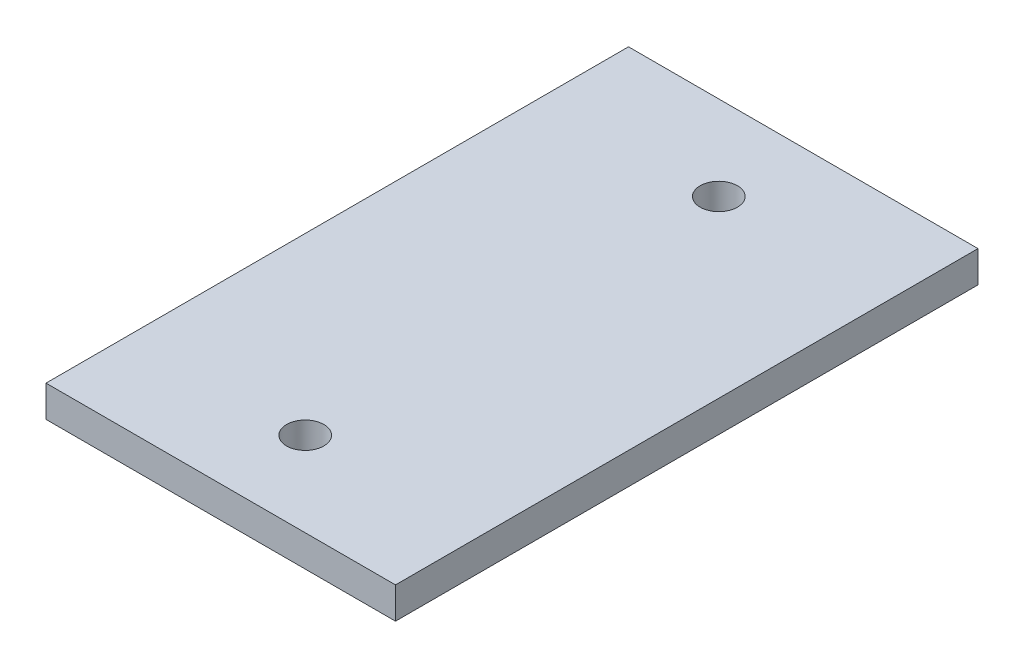
SolidWorks part; units mm, degrees
ref_plane "Front Plane" through (0, 0, 0) normal (0, 0, 1) x (1, 0, 0)
ref_plane "Top Plane" through (0, 0, 0) normal (0, 1, 0) x (1, 0, 0)
ref_plane "Right Plane" through (0, 0, 0) normal (1, 0, 0) x (0, 0, -1)
sketch "Sketch1" plane through (0, 0, 0) normal (0, 1, 0) x (1, 0, 0)
  line L0 (0, -2.0528) -> (0, 25.6838) construction
  line L1 (-15, 25) -> (15, 25)
  line L2 (-15, 25) -> (-15, -25)
  line L3 (-15, -25) -> (15, -25)
  line L4 (15, 25) -> (15, -25)
  line L5 (-15, 25) -> (15, -25) construction
  line L6 (-15, -25) -> (15, 25) construction
  line L7 (0, 0) -> (-35.0245, 0) construction
  circle A0 centre (0, 17.75) radius 1.6
  circle A1 centre (0, -17.75) radius 1.6
  point P0 (0, 0)
  dimension "D3" = 7.25
  dimension "D1" = 50
  dimension "D2" = 30
extrude "Boss-Extrude1" add sketch "Sketch1" along normal blind 2.7
